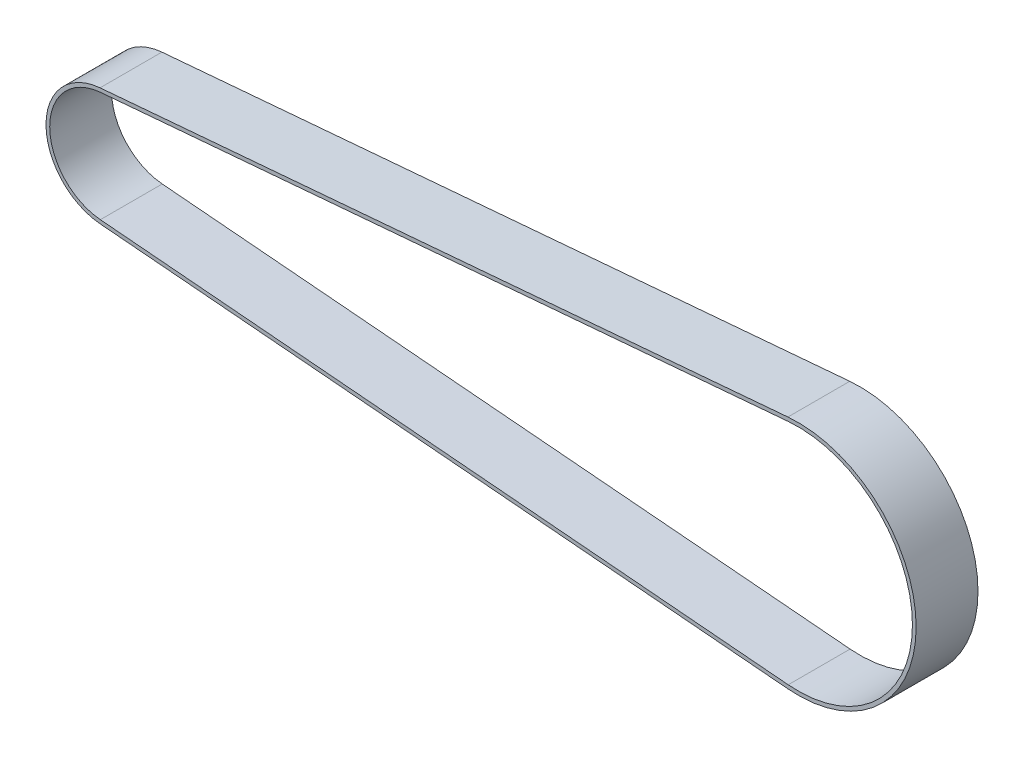
SolidWorks part; units mm, degrees
ref_plane "Front Plane" through (0, 0, 0) normal (0, 0, 1) x (1, 0, 0)
ref_plane "Top Plane" through (0, 0, 0) normal (0, 1, 0) x (1, 0, 0)
ref_plane "Right Plane" through (0, 0, 0) normal (1, 0, 0) x (0, 0, -1)
sketch "Sketch1" plane through (0, 0, 0) normal (0, 0, 1) x (1, 0, 0)
  line L0 (-2.0353, 23.7881) -> (275.9297, 47.5712)
  line L3 (275.9297, -47.5712) -> (-2.0353, -23.7881)
  line L4 (0, 0) -> (280, 0) construction
  line L5 (-1.9075, 22.2935) -> (276.0576, 46.0766)
  line L6 (276.0576, -46.0766) -> (-1.9075, -22.2935)
  arc A2 (275.9297, 47.5712) -> (275.9297, -47.5712) centre (280, 0) cw
  arc A3 (-2.0353, 23.7881) -> (-2.0353, -23.7881) centre (0, 0) ccw
  arc A4 (276.0576, 46.0766) -> (276.0576, -46.0766) centre (280, 0) cw
  arc A5 (-1.9075, 22.2935) -> (-1.9075, -22.2935) centre (0, 0) ccw
  dimension "D1" = 23.875
  dimension "D2" = 47.745
  dimension "D3" = 280
  dimension "D4" = 1.5
extrude "Boss-Extrude1" add sketch "Sketch1" along normal blind 25
